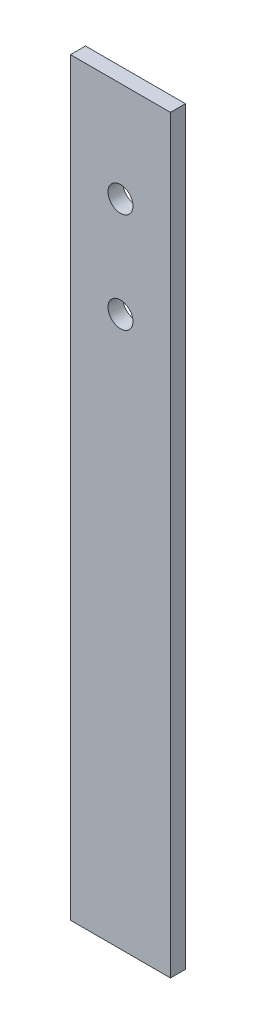
SolidWorks part; units mm, degrees
ref_plane "Top plane" through (0, 0, 0) normal (0, 0, 1) x (1, 0, 0)
ref_plane "Right plane" through (0, 0, 0) normal (0, 1, 0) x (1, 0, 0)
ref_plane "Front plane" through (0, 0, 0) normal (1, 0, 0) x (0, 0, -1)
sketch "Sketch1" plane through (0, 0, 0) normal (0, 0, 1) x (1, 0, 0)
  line L1 (72.4693, 114.0117) -> (92.4693, 114.0117)
  line L2 (72.4693, 114.0117) -> (72.4693, -35.9883)
  line L3 (72.4693, -35.9883) -> (92.4693, -35.9883)
  line L4 (92.4693, 114.0117) -> (92.4693, -35.9883)
  line L5 (72.4693, 114.0117) -> (92.4693, -35.9883) construction
  line L6 (72.4693, -35.9883) -> (92.4693, 114.0117) construction
  circle A0 centre (82.4693, 94.0117) radius 2.5
  circle A1 centre (82.4693, 74.0117) radius 2.5
  point P0 (82.4693, 39.0117)
  dimension "D3" = 5
  dimension "D4" = 20
  dimension "5" = 5
  dimension "D1" = 20
  dimension "D2" = 150
  dimension "D5" = 40
extrude "Boss-Extrude1" add sketch "Sketch1" along normal blind 3 contours L4 L1 L2 L3 A1 A0
